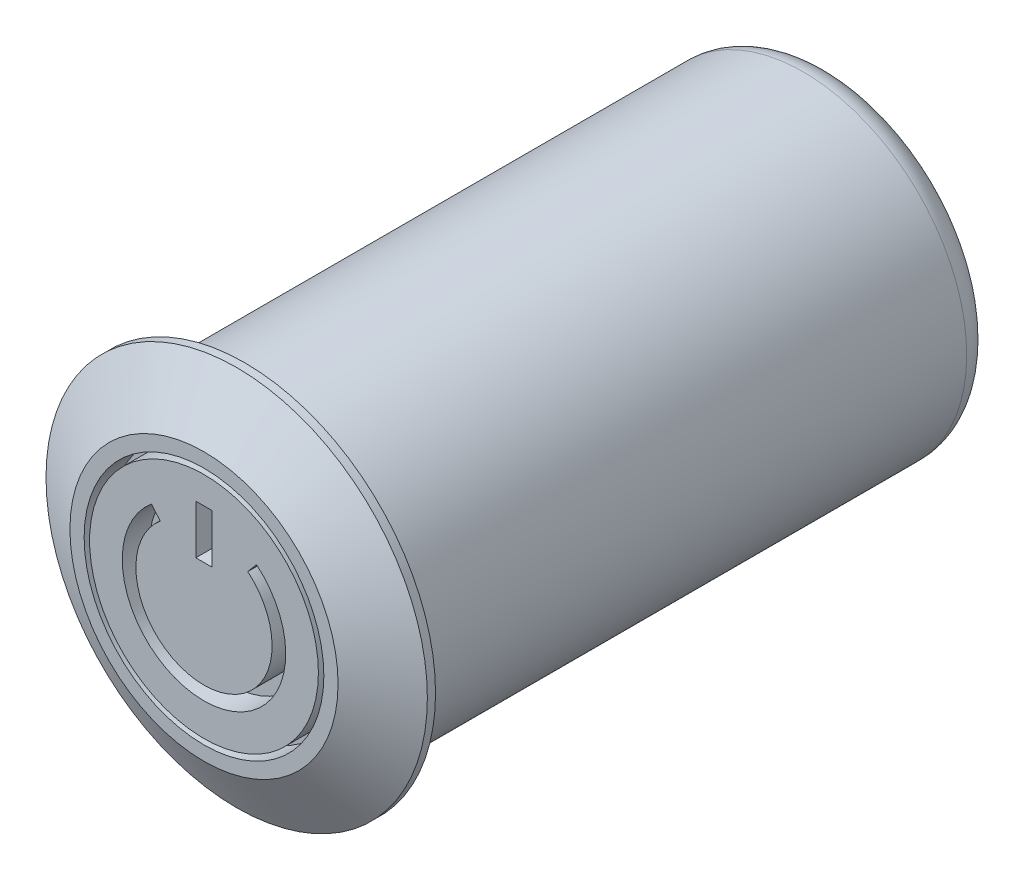
SolidWorks part; units mm, degrees
ref_plane "前视基准面" through (0, 0, 0) normal (0, 0, 1) x (1, 0, 0)
ref_plane "上视基准面" through (0, 0, 0) normal (0, 1, 0) x (1, 0, 0)
ref_plane "右视基准面" through (0, 0, 0) normal (1, 0, 0) x (0, 0, -1)
sketch "草图1" plane through (0, 0, 0) normal (0, 0, 1) x (1, 0, 0)
  circle A0 centre (0, 0) radius 7
extrude "凸台-拉伸1" add sketch "草图1" along normal blind 1.5
chamfer "倒角1" distance 1.2 angle 60 1 edges at (7, 0, 1.5)
sketch "草图2" plane through (0, 0, 1.5) normal (0, 0, 1) x (1, 0, 0)
  line L1 (0, 3.2) -> (0.3, 3.2)
  line L2 (0, 3.2) -> (-0.3, 3.2)
  line L3 (-0.3, 3.2) -> (-0.3, 1.4)
  line L4 (-0.3, 1.4) -> (0.3, 1.4)
  line L5 (0.3, 1.4) -> (0.3, 3.2)
  line L6 (1.607, 1.9151) -> (1.9284, 2.2981)
  line L7 (-1.607, 1.9151) -> (-1.9284, 2.2981)
  circle A0 centre (0, 0) radius 4.4
  circle A1 centre (0, 0) radius 4.2
  arc A2 (-1.607, 1.9151) -> (1.607, 1.9151) centre (0, 0) ccw
  arc A3 (-1.9284, 2.2981) -> (1.9284, 2.2981) centre (0, 0) ccw
extrude "切除-拉伸1" cut sketch "草图2" against normal blind 1 contours L4 L5 L1 L2 L3 | L7 A3 L6 A2 | A0 A1
sketch "草图3" plane through (0, 0, 0) normal (0, 0, -1) x (-1, 0, 0)
  circle A0 centre (0, 0) radius 6
extrude "凸台-拉伸2" add sketch "草图3" along normal blind 21.5
fillet "圆角1" radius 1 1 edges at (-6, 0, -21.5)
